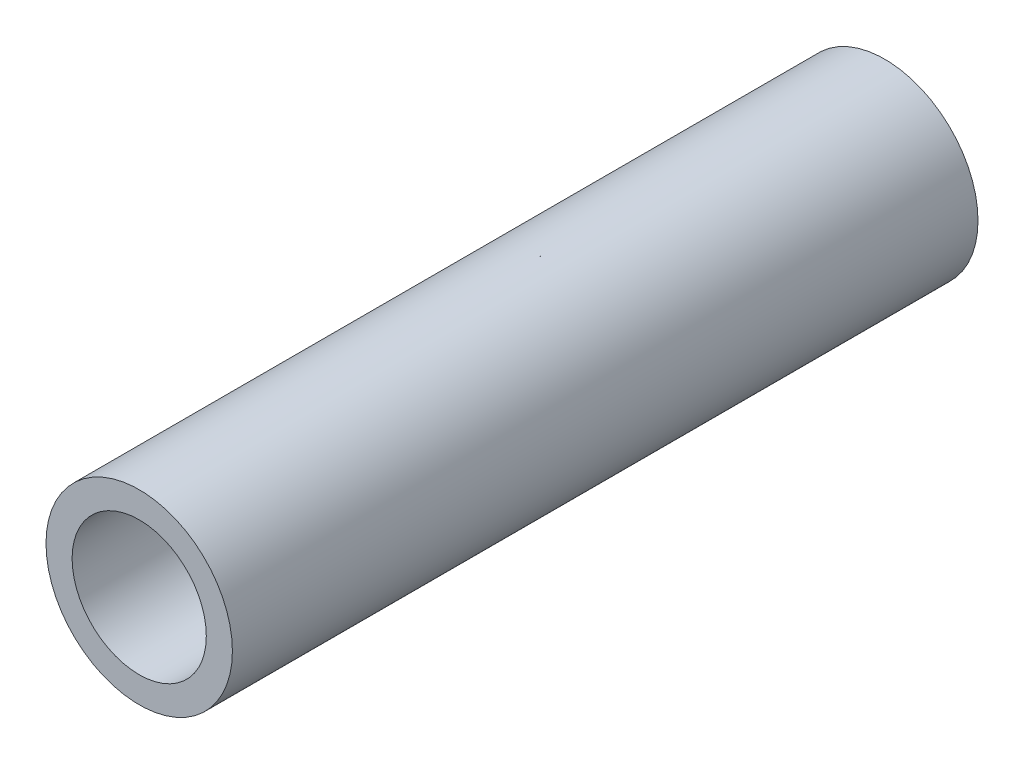
SolidWorks part; units mm, degrees
ref_plane "Alzado" through (0, 0, 0) normal (0, 0, 1) x (1, 0, 0)
ref_plane "Planta" through (0, 0, 0) normal (0, 1, 0) x (1, 0, 0)
ref_plane "Vista lateral" through (0, 0, 0) normal (1, 0, 0) x (0, 0, -1)
sketch "Croquis1" plane through (0, 0, 0) normal (0, 0, 1) x (1, 0, 0)
  circle A0 centre (0, 0) radius 1.8
  circle A1 centre (0, 0) radius 2.5
  dimension "D1" = 3.6
  dimension "D2" = 5
extrude "Saliente-Extruir1" add sketch "Croquis1" along normal blind 20
sketch "Croquis2" plane through (0, 0, 20) normal (0, 0, 1) x (1, 0, 0)
  line L0 (-1.8, 0) -> (1.8, 0) construction
  line L1 (0, -1.8) -> (0, 1.8) construction
  circle A0 centre (0, 0) radius 1.8 construction
  point P8 (0, 0)
  point P13 (0, 0)
sketch "Croquis3" plane through (0, 0, 0) normal (0, 0, -1) x (-1, 0, 0)
  circle A0 centre (0, 0) radius 1.8
extrude "Saliente-Extruir2" add sketch "Croquis3" against normal blind 3.15
sketch "Croquis4" plane through (0, 0, 0) normal (0, 0, -1) x (-1, 0, 0)
  line L0 (0, -1.8) -> (0, 1.8) construction
  circle A0 centre (0, 0) radius 1.12
  dimension "D1" = 2.24
extrude "Cortar-Extruir1" cut sketch "Croquis4" against normal through all both and the other way through all
